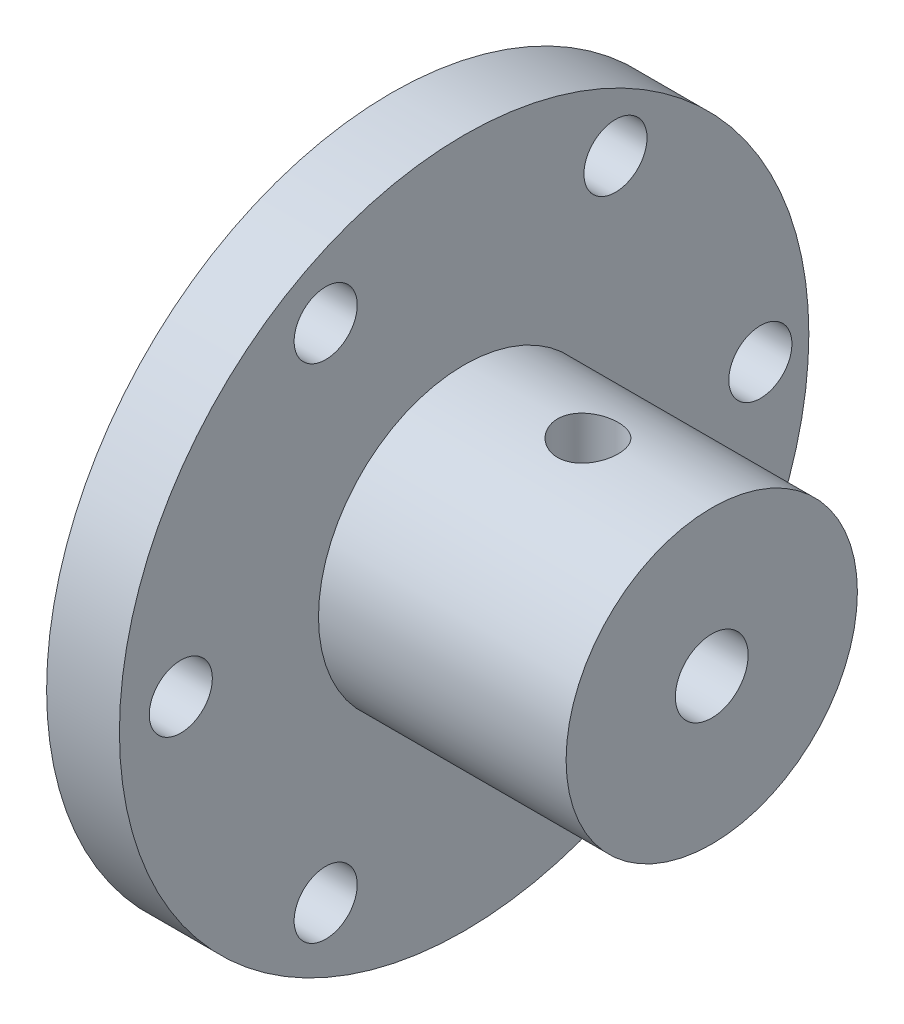
SolidWorks part; units mm, degrees
ref_plane "Plan de face" through (0, 0, 0) normal (0, 0, 1) x (1, 0, 0)
ref_plane "Plan de dessus" through (0, 0, 0) normal (0, 1, 0) x (1, 0, 0)
ref_plane "Plan de droite" through (0, 0, 0) normal (1, 0, 0) x (0, 0, -1)
sketch "Esquisse1" plane through (0, 0, 0) normal (0, 0, 1) x (1, 0, 0)
  line L0 (54.3675, 0) -> (-231.2033, 0) construction
  line L1 (-39.661, 12) -> (-60.061, 12)
  line L2 (-60.061, 12) -> (-60.061, 28.4)
  line L3 (-60.061, 28.4) -> (-66.061, 28.4)
  line L4 (-66.061, 28.4) -> (-66.061, 3)
  line L5 (-66.061, 3) -> (-39.661, 3)
  line L6 (-39.661, 3) -> (-39.661, 12)
  point P5 (-88.4179, 0)
  dimension "D1" = 9
  dimension "D2" = 3
  dimension "D3" = 26.4
  dimension "D4" = 6
  dimension "D5" = 28.4
revolve "Révolution1" add sketch "Esquisse1" angle 360 about L0
sketch "Esquisse2" plane through (-60.061, 0, 0) normal (1, 0, 0) x (0, 0, -1)
  line L0 (0, 30.9823) -> (0, -32.549) construction
  line L1 (-36.5051, 0) -> (31.1782, 0) construction
  circle A0 centre (-23.3444, 0) radius 2.6
  circle A1 centre (-11.4069, 20.6764) radius 2.6
  circle A2 centre (12.4681, 20.6764) radius 2.6
  circle A3 centre (24.4056, 0) radius 2.6
  circle A4 centre (12.4681, -20.6764) radius 2.6
  circle A5 centre (-11.4069, -20.6764) radius 2.6
  point P19 (0.5306, 0)
  dimension "D1" = 6
  dimension "D2" = 23.875
extrude "Enlèv. mat.-Extru.1" cut sketch "Esquisse2" against normal blind 10
ref_plane "Plan1" through (0, 12, 0) normal (0, -1, 0) x (-1, 0, 0)
sketch "Esquisse3" plane through (0, 12, 0) normal (0, -1, 0) x (-1, 0, 0)
  line L0 (39.661, 0) -> (60.061, 0) construction
  line L1 (39.661, 12) -> (39.661, -12) construction
  circle A0 centre (49.861, 0) radius 2.5
  dimension "D1" = 10.2
extrude "Enlèv. mat.-Extru.2" cut sketch "Esquisse3" along normal blind 10
